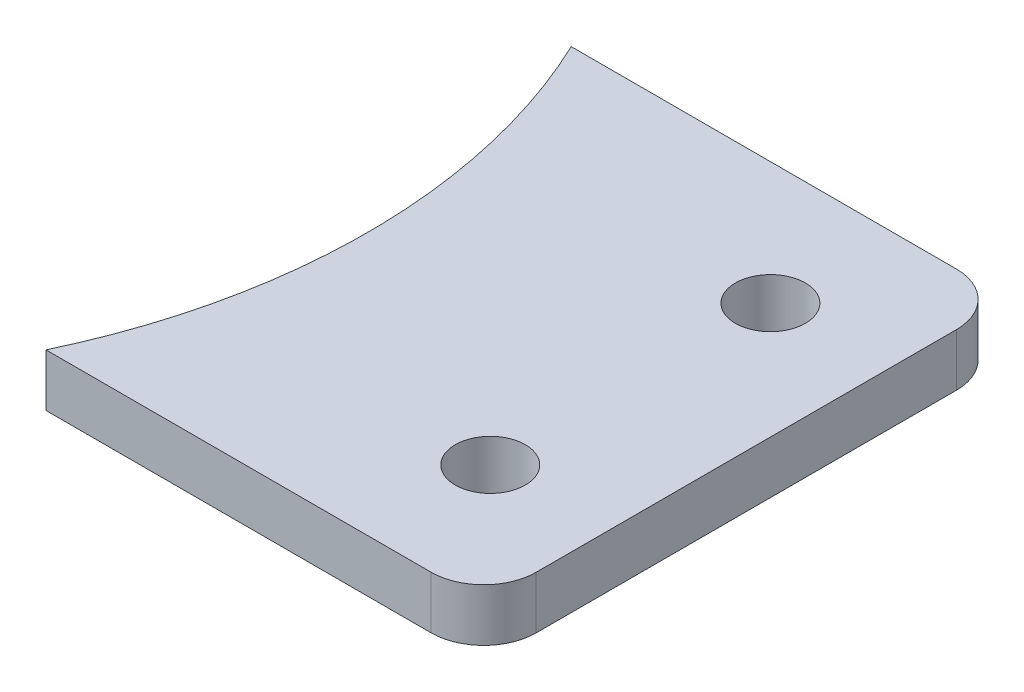
SolidWorks part; units mm, degrees
material "Thornel Mat VMA"
ref_plane "前视基准面" through (0, 0, 0) normal (0, 0, 1) x (1, 0, 0)
ref_plane "上视基准面" through (0, 0, 0) normal (0, 1, 0) x (1, 0, 0)
ref_plane "右视基准面" through (0, 0, 0) normal (1, 0, 0) x (0, 0, -1)
other "Configuration Table"
sketch "草图1" plane through (0, 0, 0) normal (0, 1, 0) x (1, 0, 0)
  line L0 (0, 0) -> (0, 50.2684) construction
  line L1 (0, 0) -> (70.4502, 0) construction
  line L2 (31.6228, 15) -> (56.6228, 15)
  line L3 (56.6228, 15) -> (56.6228, -15)
  line L4 (31.6228, -15) -> (56.6228, -15)
  circle A0 centre (0, 0) radius 35 construction
  arc A1 (31.6228, -15) -> (31.6228, 15) centre (0, 0) ccw
  circle A3 centre (50, 8) radius 2
  circle A4 centre (50, -8) radius 2
  point P10 (56.6228, 0)
  dimension "D1" = 70
  dimension "D4" = 4
  dimension "D5" = 8
  dimension "D2" = 15
  dimension "D3" = 25
  dimension "D6" = 50
extrude "凸台-拉伸1" add sketch "草图1" along normal blind 3
fillet "圆角1" radius 3 2 edges at (56.6228, 1.5, 15) (56.6228, 1.5, -15)
